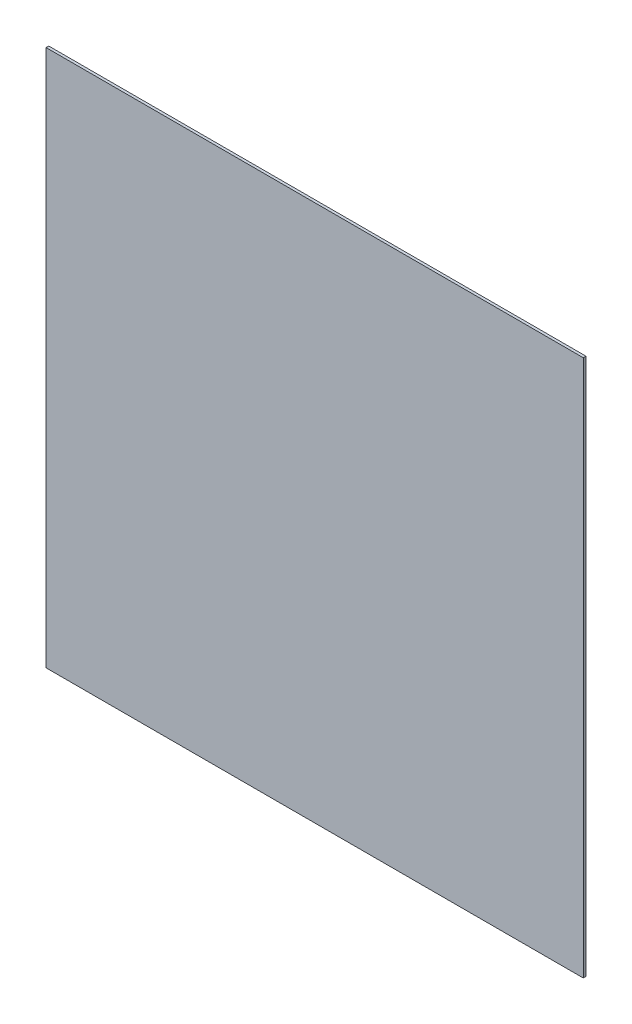
SolidWorks part; units mm, degrees
ref_plane "Front Plane" through (0, 0, 0) normal (0, 0, 1) x (1, 0, 0)
ref_plane "Top Plane" through (0, 0, 0) normal (0, 1, 0) x (1, 0, 0)
ref_plane "Right Plane" through (0, 0, 0) normal (1, 0, 0) x (0, 0, -1)
other "Configuration Table"
sketch "Sketch1" plane through (0, 0, 0) normal (0, 0, 1) x (1, 0, 0)
  line L1 (0, 41.6) -> (320, 41.6)
  line L2 (0, 41.6) -> (0, 361.6)
  line L3 (0, 361.6) -> (320, 361.6)
  line L4 (320, 41.6) -> (320, 361.6)
extrude "KUTU_kapak_320x320_dik_1" add sketch "Sketch1" against normal blind 1.6 from offset 320 separate body
